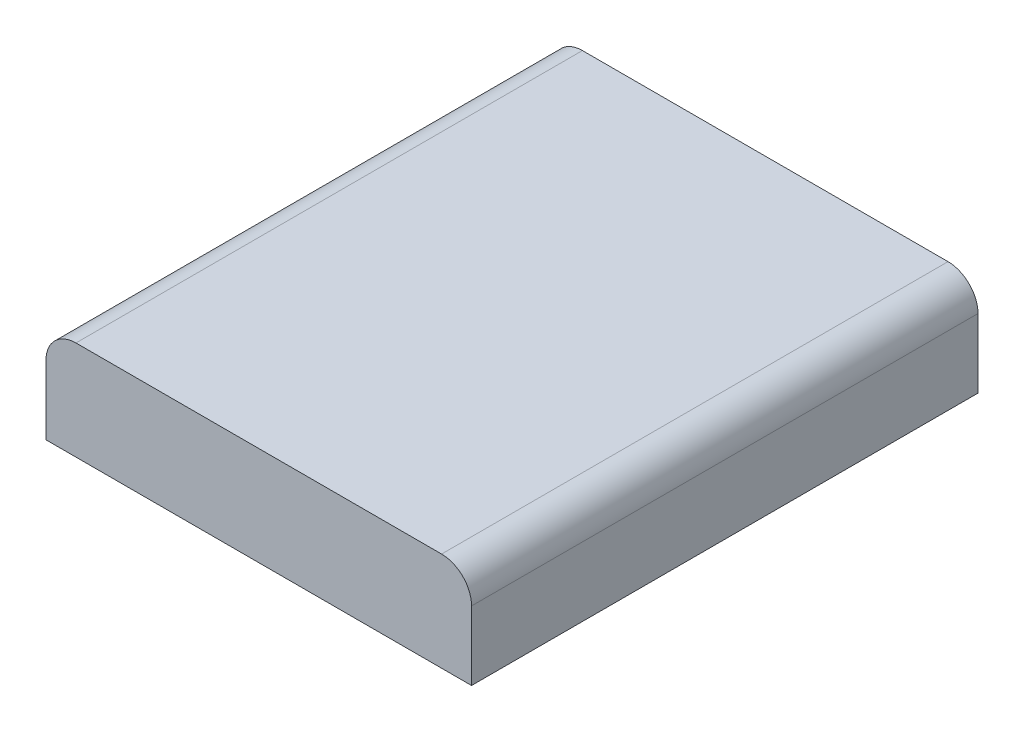
SolidWorks part; units mm, degrees
material "PEI"
ref_plane "前视基准面" through (0, 0, 0) normal (0, 0, 1) x (1, 0, 0)
ref_plane "上视基准面" through (0, 0, 0) normal (0, 1, 0) x (1, 0, 0)
ref_plane "右视基准面" through (0, 0, 0) normal (1, 0, 0) x (0, 0, -1)
other "Configuration Table"
sketch "草图1" plane through (0, 0, 0) normal (0, 0, 1) x (1, 0, 0)
  line L1 (0, 0) -> (142, 0)
  line L2 (0, 0) -> (0, 23)
  line L3 (10, 33) -> (132, 33)
  line L4 (142, 0) -> (142, 23)
  line L5 (0, 0) -> (142, 33) construction
  line L6 (0, 33) -> (142, 0) construction
  arc A0 (142, 23) -> (132, 33) centre (132, 23) ccw
  arc A1 (10, 33) -> (0, 23) centre (10, 23) ccw
  point P4 (71, 16.5)
  dimension "D3" = 10
  dimension "D1" = 33
  dimension "D2" = 142
extrude "凸台-拉伸1" add sketch "草图1" along normal blind 169
